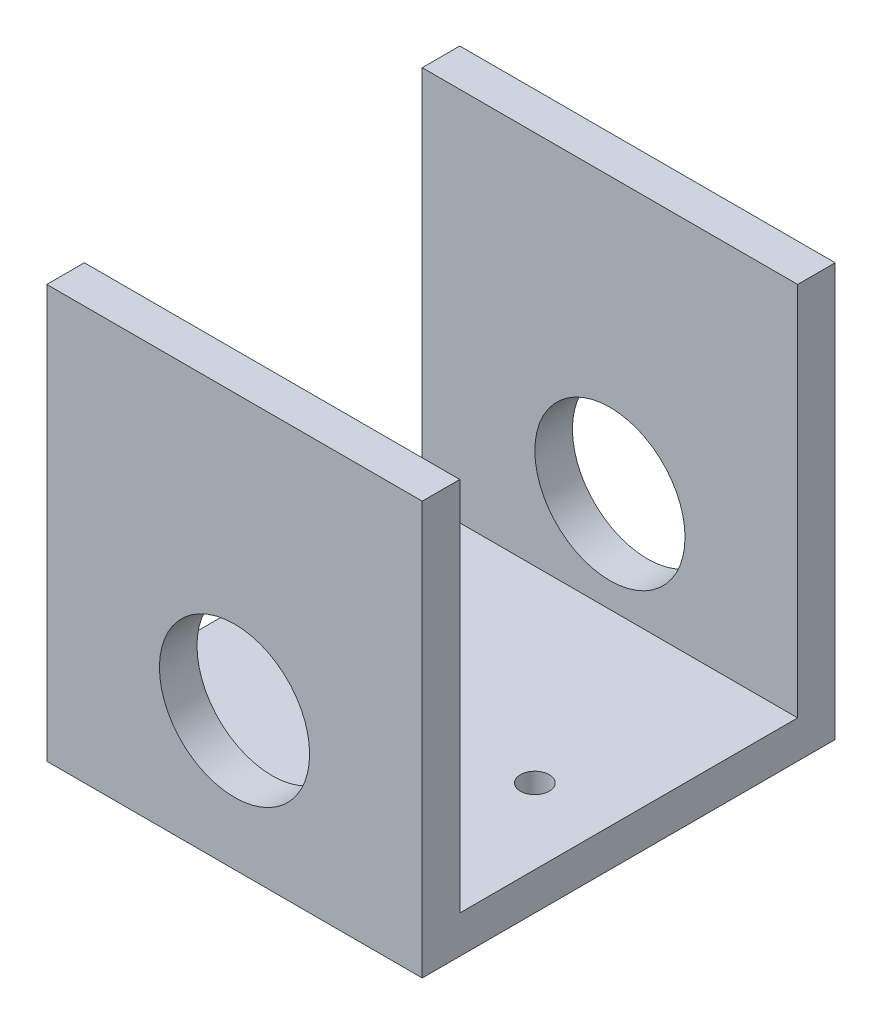
SolidWorks part; units mm, degrees
ref_plane "Front Plane" through (0, 0, 0) normal (0, 0, 1) x (1, 0, 0)
ref_plane "Top Plane" through (0, 0, 0) normal (0, 1, 0) x (1, 0, 0)
ref_plane "Right Plane" through (0, 0, 0) normal (1, 0, 0) x (0, 0, -1)
sketch "Sketch1" plane through (0, 0, 0) normal (0, 1, 0) x (1, 0, 0)
  line L1 (0, 0) -> (30, 0)
  line L2 (0, 0) -> (0, 30)
  line L3 (0, 30) -> (30, 30)
  line L4 (30, 0) -> (30, 30)
  circle A0 centre (6, 12) radius 1.15
  circle A1 centre (24, 12) radius 1.15
  dimension "D2" = 2.3
  dimension "D3" = 2.3
  dimension "D4" = 18
  dimension "D7" = 18
  dimension "D1" = 30
  dimension "D5" = 6
  dimension "D6" = 30
extrude "Boss-Extrude1" add sketch "Sketch1" along normal blind 3
sketch "Sketch2" plane through (0, 3, 0) normal (0, 1, 0) x (1, 0, 0)
  line L0 (0, 30) -> (0, 0) construction
  line L1 (30, 30) -> (0, 30)
  line L2 (30, 30) -> (30, 27)
  line L3 (30, 27) -> (0, 27)
  line L4 (0, 30) -> (0, 27)
  dimension "D1" = 3
extrude "Boss-Extrude2" add sketch "Sketch2" along normal blind 30
sketch "Sketch3" plane through (0, 0, -30) normal (0, 0, -1) x (-1, 0, 0)
  line L0 (-30, 0) -> (0, 0) construction
  line L1 (-30, 33) -> (-30, 0) construction
  circle A0 centre (-15, 11) radius 6
  dimension "D1" = 11
  dimension "D2" = 12
  dimension "D3" = 15
extrude "Cut-Extrude1" cut sketch "Sketch3" against normal up to next
sketch "Sketch4" plane through (0, 0, 0) normal (0, 0, 1) x (1, 0, 0)
  line L1 (30, 0) -> (0, 0)
  line L2 (30, 0) -> (30, 33)
  line L3 (30, 33) -> (0, 33)
  line L4 (0, 0) -> (0, 33)
  circle A0 centre (15, 11) radius 6
  dimension "D2" = 12
  dimension "D1" = 33
extrude "Boss-Extrude3" add sketch "Sketch4" along normal blind 3
